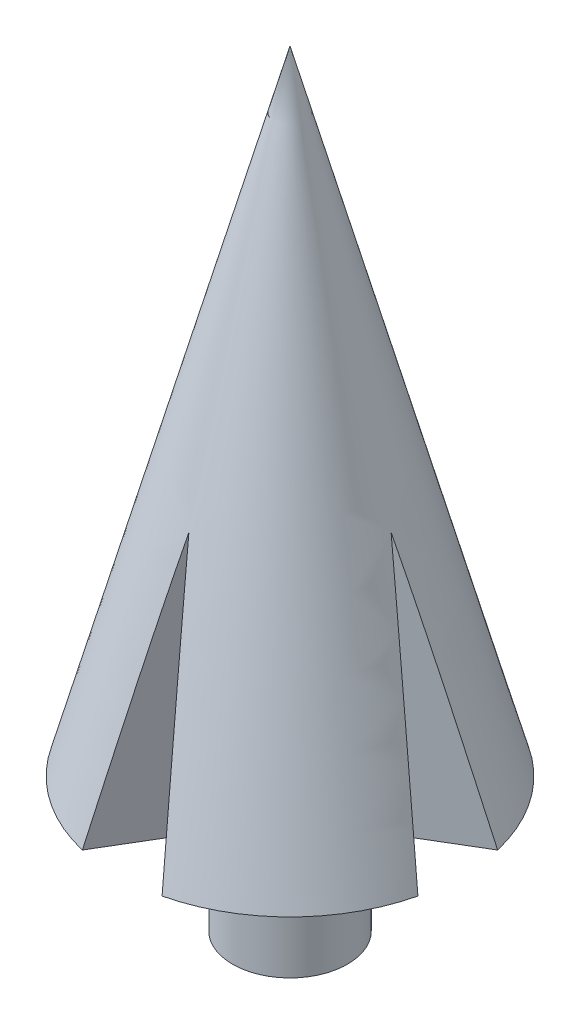
SolidWorks part; units mm, degrees
ref_plane "Front Plane" through (0, 0, 0) normal (0, 0, 1) x (1, 0, 0)
ref_plane "Top Plane" through (0, 0, 0) normal (0, 1, 0) x (1, 0, 0)
ref_plane "Right Plane" through (0, 0, 0) normal (1, 0, 0) x (0, 0, -1)
sketch "Sketch1" plane through (0, 0, 0) normal (0, 0, 1) x (1, 0, 0)
  line L1 (-3, 0) -> (-3, 7)
  line L2 (-3, 7) -> (-9, 7)
  line L3 (-9, 7) -> (0, 40)
  line L4 (0, 40) -> (0, 0)
  line L5 (-3, 0) -> (0, 0)
  dimension "D1" = 3
  dimension "D2" = 6
  dimension "D3" = 40
  dimension "D4" = 7
revolve "Revolve1" add sketch "Sketch1" angle 360 about L4
sketch "Sketch2" plane through (0, 7, 0) normal (0, -1, 0) x (1, 0, 0)
  line L0 (-2.0797, 8.7564) -> (0, 5.2742)
  line L1 (0, 5.2742) -> (2.0797, 8.7564)
  line L2 (8.7564, 2.0797) -> (5.2742, 0)
  line L3 (5.2742, 0) -> (8.7564, -2.0797)
  line L4 (2.0797, -8.7564) -> (0, -5.2742)
  line L5 (0, -5.2742) -> (-2.0797, -8.7564)
  line L6 (-8.7564, -2.0797) -> (-5.2742, 0)
  line L7 (-5.2742, 0) -> (-8.7564, 2.0797)
  circle A1 centre (0, 0) radius 9 construction
  arc A2 (-2.0797, 8.7564) -> (2.0797, 8.7564) centre (0, 5.2742) cw
  arc A3 (8.7564, 2.0797) -> (8.7564, -2.0797) centre (5.2742, 0) cw
  arc A4 (2.0797, -8.7564) -> (-2.0797, -8.7564) centre (0, -5.2742) cw
  arc A5 (-8.7564, -2.0797) -> (-8.7564, 2.0797) centre (-5.2742, 0) cw
  dimension "D1" = 4
extrude "Cut-Extrude1" cut sketch "Sketch2" against normal blind 15
